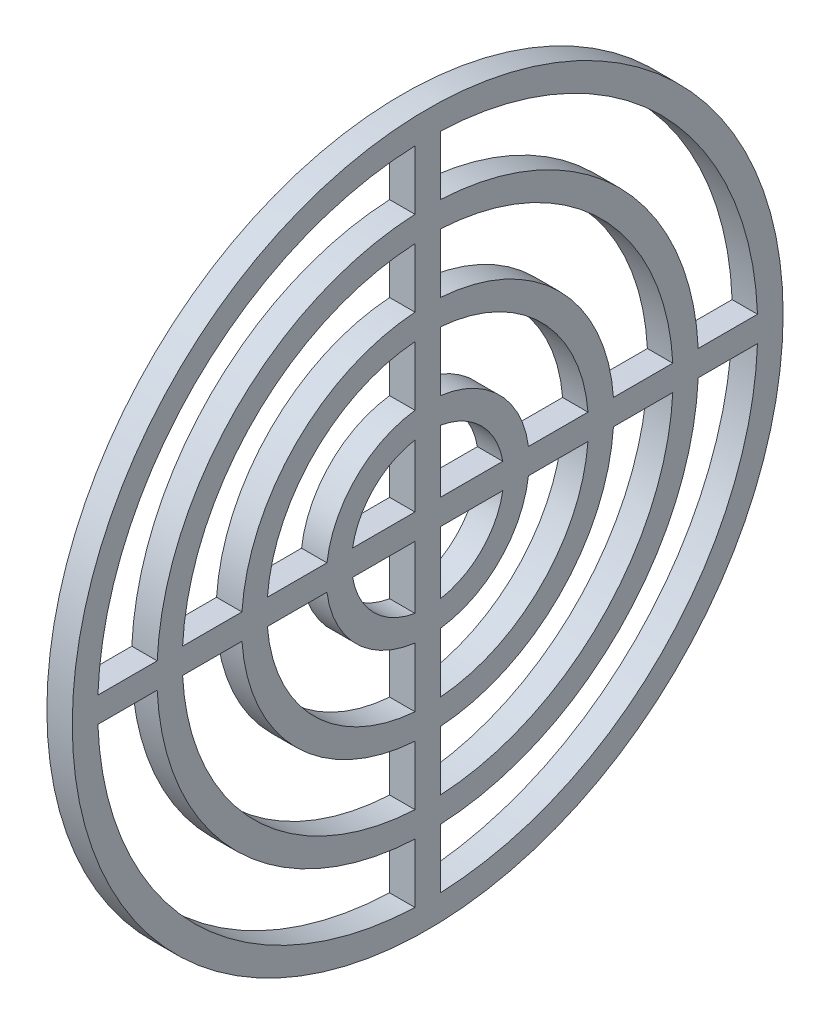
SolidWorks part; units mm, degrees
ref_plane "Front Plane" through (0, 0, 0) normal (0, 0, 1) x (1, 0, 0)
ref_plane "Top Plane" through (0, 0, 0) normal (0, 1, 0) x (1, 0, 0)
ref_plane "Right Plane" through (0, 0, 0) normal (1, 0, 0) x (0, 0, -1)
sketch "Sketch1" plane through (0, 0, 0) normal (1, 0, 0) x (0, 0, -1)
  line L0 (0, 65.1905) -> (0, 12) construction
  line L1 (-52.0764, 0) -> (50.4083, 0) construction
  line L2 (-1.5, 38.9711) -> (-1.5, 31.9648)
  line L3 (1.5, 38.9711) -> (1.5, 31.9648)
  line L4 (38.9711, -1.5) -> (31.9648, -1.5)
  line L5 (38.9711, 1.5) -> (31.9648, 1.5)
  line L6 (-1.5, -38.9711) -> (-1.5, -31.9648)
  line L7 (1.5, -38.9711) -> (1.5, -31.9648)
  line L8 (-38.9711, 1.5) -> (-31.9648, 1.5)
  line L9 (-38.9711, -1.5) -> (-31.9648, -1.5)
  line L10 (-1.5, 1.5) -> (0, 1.5) construction
  line L11 (-1.5, 1.5) -> (-1.5, 0) construction
  line L12 (-1.5, -1.5) -> (-1.5, 0) construction
  line L13 (-1.5, -1.5) -> (0, -1.5) construction
  line L14 (1.5, -1.5) -> (0, -1.5) construction
  line L15 (1.5, -1.5) -> (1.5, 0) construction
  line L16 (1.5, 1.5) -> (0, 1.5) construction
  line L17 (1.5, 1.5) -> (1.5, 0) construction
  line L18 (-31.9648, 1.5) -> (-28.9612, 1.5) construction
  line L19 (-28.9612, 1.5) -> (-21.9488, 1.5)
  line L20 (-21.9488, 1.5) -> (-18.9407, 1.5) construction
  line L21 (-18.9407, 1.5) -> (-11.9059, 1.5)
  line L22 (-11.9059, 1.5) -> (-8.8741, 1.5) construction
  line L23 (-8.8741, 1.5) -> (-1.5, 1.5)
  line L24 (-31.9648, -1.5) -> (-28.9612, -1.5) construction
  line L25 (-28.9612, -1.5) -> (-21.9488, -1.5)
  line L26 (-21.9488, -1.5) -> (-18.9407, -1.5) construction
  line L27 (-18.9407, -1.5) -> (-11.9059, -1.5)
  line L28 (-11.9059, -1.5) -> (-8.8741, -1.5) construction
  line L29 (-8.8741, -1.5) -> (-1.5, -1.5)
  line L30 (-1.5, -11.9059) -> (-1.5, -8.8741) construction
  line L31 (-1.5, -8.8741) -> (-1.5, -1.5)
  line L32 (-1.5, -21.9488) -> (-1.5, -18.9407) construction
  line L33 (-1.5, -18.9407) -> (-1.5, -11.9059)
  line L34 (-1.5, -31.9648) -> (-1.5, -28.9612) construction
  line L35 (-1.5, -28.9612) -> (-1.5, -21.9488)
  line L36 (1.5, -31.9648) -> (1.5, -28.9612) construction
  line L37 (1.5, -28.9612) -> (1.5, -21.9488)
  line L38 (1.5, -21.9488) -> (1.5, -18.9407) construction
  line L39 (1.5, -18.9407) -> (1.5, -11.9059)
  line L40 (1.5, -11.9059) -> (1.5, -8.8741) construction
  line L41 (1.5, -8.8741) -> (1.5, -1.5)
  line L42 (11.9059, -1.5) -> (8.8741, -1.5) construction
  line L43 (8.8741, -1.5) -> (1.5, -1.5)
  line L44 (11.9059, 1.5) -> (8.8741, 1.5) construction
  line L45 (8.8741, 1.5) -> (1.5, 1.5)
  line L46 (21.9488, -1.5) -> (18.9407, -1.5) construction
  line L47 (18.9407, -1.5) -> (11.9059, -1.5)
  line L48 (21.9488, 1.5) -> (18.9407, 1.5) construction
  line L49 (18.9407, 1.5) -> (11.9059, 1.5)
  line L50 (31.9648, 1.5) -> (28.9612, 1.5) construction
  line L51 (28.9612, 1.5) -> (21.9488, 1.5)
  line L52 (31.9648, -1.5) -> (28.9612, -1.5) construction
  line L53 (28.9612, -1.5) -> (21.9488, -1.5)
  line L54 (-1.5, 31.9648) -> (-1.5, 28.9612) construction
  line L55 (-1.5, 28.9612) -> (-1.5, 21.9488)
  line L56 (-1.5, 21.9488) -> (-1.5, 18.9407) construction
  line L57 (-1.5, 18.9407) -> (-1.5, 11.9059)
  line L58 (-1.5, 11.9059) -> (-1.5, 8.8741) construction
  line L59 (-1.5, 8.8741) -> (-1.5, 1.5)
  line L60 (1.5, 31.9648) -> (1.5, 28.9612) construction
  line L61 (1.5, 28.9612) -> (1.5, 21.9488)
  line L62 (1.5, 21.9488) -> (1.5, 18.9407) construction
  line L63 (1.5, 18.9407) -> (1.5, 11.9059)
  line L64 (1.5, 11.9059) -> (1.5, 8.8741) construction
  line L65 (1.5, 8.8741) -> (1.5, 1.5)
  line L66 (0, 12) -> (0, 9) construction
  line L67 (0, 9) -> (0, -59.8179) construction
  circle A0 centre (0, 0) radius 42
  arc A1 (-1.5, 38.9711) -> (-38.9711, 1.5) centre (0, 0) ccw
  arc A2 (0, 39) -> (-1.5, 38.9711) centre (0, 0) ccw construction
  arc A3 (1.5, 38.9711) -> (0, 39) centre (0, 0) ccw construction
  arc A4 (39, 0) -> (38.9711, 1.5) centre (0, 0) ccw construction
  arc A5 (38.9711, 1.5) -> (1.5, 38.9711) centre (0, 0) ccw
  arc A6 (38.9711, -1.5) -> (39, 0) centre (0, 0) ccw construction
  arc A7 (-1.5, -38.9711) -> (0, -39) centre (0, 0) ccw construction
  arc A8 (1.5, -38.9711) -> (38.9711, -1.5) centre (0, 0) ccw
  arc A9 (0, -39) -> (1.5, -38.9711) centre (0, 0) ccw construction
  arc A10 (-39, 0) -> (-38.9711, -1.5) centre (0, 0) ccw construction
  arc A11 (-38.9711, -1.5) -> (-1.5, -38.9711) centre (0, 0) ccw
  arc A12 (-38.9711, 1.5) -> (-39, 0) centre (0, 0) ccw construction
  arc A13 (-31.9648, -1.5) -> (-1.5, -31.9648) centre (0, 0) ccw
  arc A14 (-21.9488, -1.5) -> (-1.5, -21.9488) centre (0, 0) ccw
  arc A15 (-11.9059, -1.5) -> (-1.5, -11.9059) centre (0, 0) ccw
  arc A16 (-28.9612, -1.5) -> (-1.5, -28.9612) centre (0, 0) ccw
  arc A17 (-18.9407, -1.5) -> (-1.5, -18.9407) centre (0, 0) ccw
  arc A18 (-8.8741, -1.5) -> (-1.5, -8.8741) centre (0, 0) ccw
  arc A19 (-31.9648, 1.5) -> (-32, 0) centre (0, 0) ccw construction
  circle A20 centre (0, 0) radius 32 construction
  arc A21 (-28.9612, 1.5) -> (-29, 0) centre (0, 0) ccw construction
  circle A22 centre (0, 0) radius 29 construction
  arc A23 (-21.9488, 1.5) -> (-22, 0) centre (0, 0) ccw construction
  circle A24 centre (0, 0) radius 22 construction
  arc A25 (-18.9407, 1.5) -> (-19, 0) centre (0, 0) ccw construction
  circle A26 centre (0, 0) radius 19 construction
  arc A27 (-11.9059, 1.5) -> (-12, 0) centre (0, 0) ccw construction
  circle A28 centre (0, 0) radius 12 construction
  arc A29 (-8.8741, 1.5) -> (-9, 0) centre (0, 0) ccw construction
  circle A30 centre (0, 0) radius 9 construction
  arc A31 (-32, 0) -> (-31.9648, -1.5) centre (0, 0) ccw construction
  arc A32 (-29, 0) -> (-28.9612, -1.5) centre (0, 0) ccw construction
  arc A33 (-22, 0) -> (-21.9488, -1.5) centre (0, 0) ccw construction
  arc A34 (-19, 0) -> (-18.9407, -1.5) centre (0, 0) ccw construction
  arc A35 (-12, 0) -> (-11.9059, -1.5) centre (0, 0) ccw construction
  arc A36 (-9, 0) -> (-8.8741, -1.5) centre (0, 0) ccw construction
  arc A37 (-1.5, -8.8741) -> (0, -9) centre (0, 0) ccw construction
  arc A38 (1.5, -8.8741) -> (8.8741, -1.5) centre (0, 0) ccw
  arc A39 (-1.5, -11.9059) -> (0, -12) centre (0, 0) ccw construction
  arc A40 (1.5, -11.9059) -> (11.9059, -1.5) centre (0, 0) ccw
  arc A41 (-1.5, -18.9407) -> (0, -19) centre (0, 0) ccw construction
  arc A42 (1.5, -18.9407) -> (18.9407, -1.5) centre (0, 0) ccw
  arc A43 (-1.5, -21.9488) -> (0, -22) centre (0, 0) ccw construction
  arc A44 (1.5, -21.9488) -> (21.9488, -1.5) centre (0, 0) ccw
  arc A45 (-1.5, -28.9612) -> (0, -29) centre (0, 0) ccw construction
  arc A46 (1.5, -28.9612) -> (28.9612, -1.5) centre (0, 0) ccw
  arc A47 (0, -32) -> (1.5, -31.9648) centre (0, 0) ccw construction
  arc A48 (1.5, -31.9648) -> (31.9648, -1.5) centre (0, 0) ccw
  arc A49 (0, -29) -> (1.5, -28.9612) centre (0, 0) ccw construction
  arc A50 (0, -22) -> (1.5, -21.9488) centre (0, 0) ccw construction
  arc A51 (0, -19) -> (1.5, -18.9407) centre (0, 0) ccw construction
  arc A52 (0, -12) -> (1.5, -11.9059) centre (0, 0) ccw construction
  arc A53 (0, -9) -> (1.5, -8.8741) centre (0, 0) ccw construction
  arc A54 (8.8741, -1.5) -> (9, 0) centre (0, 0) ccw construction
  arc A55 (8.8741, 1.5) -> (1.5, 8.8741) centre (0, 0) ccw
  arc A56 (11.9059, -1.5) -> (12, 0) centre (0, 0) ccw construction
  arc A57 (11.9059, 1.5) -> (1.5, 11.9059) centre (0, 0) ccw
  arc A58 (9, 0) -> (8.8741, 1.5) centre (0, 0) ccw construction
  arc A59 (12, 0) -> (11.9059, 1.5) centre (0, 0) ccw construction
  arc A60 (18.9407, -1.5) -> (19, 0) centre (0, 0) ccw construction
  arc A61 (18.9407, 1.5) -> (1.5, 18.9407) centre (0, 0) ccw
  arc A62 (21.9488, -1.5) -> (22, 0) centre (0, 0) ccw construction
  arc A63 (21.9488, 1.5) -> (1.5, 21.9488) centre (0, 0) ccw
  arc A64 (19, 0) -> (18.9407, 1.5) centre (0, 0) ccw construction
  arc A65 (22, 0) -> (21.9488, 1.5) centre (0, 0) ccw construction
  arc A66 (29, 0) -> (28.9612, 1.5) centre (0, 0) ccw construction
  arc A67 (28.9612, 1.5) -> (1.5, 28.9612) centre (0, 0) ccw
  arc A68 (32, 0) -> (31.9648, 1.5) centre (0, 0) ccw construction
  arc A69 (31.9648, 1.5) -> (1.5, 31.9648) centre (0, 0) ccw
  arc A70 (28.9612, -1.5) -> (29, 0) centre (0, 0) ccw construction
  arc A71 (31.9648, -1.5) -> (32, 0) centre (0, 0) ccw construction
  arc A72 (0, 32) -> (-1.5, 31.9648) centre (0, 0) ccw construction
  arc A73 (-1.5, 31.9648) -> (-31.9648, 1.5) centre (0, 0) ccw
  arc A74 (0, 29) -> (-1.5, 28.9612) centre (0, 0) ccw construction
  arc A75 (-1.5, 28.9612) -> (-28.9612, 1.5) centre (0, 0) ccw
  arc A76 (0, 22) -> (-1.5, 21.9488) centre (0, 0) ccw construction
  arc A77 (-1.5, 21.9488) -> (-21.9488, 1.5) centre (0, 0) ccw
  arc A78 (0, 19) -> (-1.5, 18.9407) centre (0, 0) ccw construction
  arc A79 (-1.5, 18.9407) -> (-18.9407, 1.5) centre (0, 0) ccw
  arc A80 (0, 12) -> (-1.5, 11.9059) centre (0, 0) ccw construction
  arc A81 (-1.5, 11.9059) -> (-11.9059, 1.5) centre (0, 0) ccw
  arc A82 (1.5, 31.9648) -> (0, 32) centre (0, 0) ccw construction
  arc A83 (1.5, 28.9612) -> (0, 29) centre (0, 0) ccw construction
  arc A84 (1.5, 21.9488) -> (0, 22) centre (0, 0) ccw construction
  arc A85 (1.5, 18.9407) -> (0, 19) centre (0, 0) ccw construction
  arc A86 (1.5, 11.9059) -> (0, 12) centre (0, 0) ccw construction
  arc A87 (0, 9) -> (-1.5, 8.8741) centre (0, 0) ccw construction
  arc A88 (-1.5, 8.8741) -> (-8.8741, 1.5) centre (0, 0) ccw
  arc A89 (1.5, 8.8741) -> (0, 9) centre (0, 0) ccw construction
  arc A90 (-1.5, -31.9648) -> (0, -32) centre (0, 0) ccw construction
  point P27 (0, 0)
  dimension "D1" = 84
  dimension "D2" = 3
  dimension "D6" = 64
  dimension "D7" = 44
  dimension "D8" = 24
  dimension "D3" = 3
  dimension "D5" = 1.5
  dimension "D9" = 3
  dimension "D4" = 4
extrude "Boss-Extrude1" add sketch "Sketch1" along normal mid plane 3
